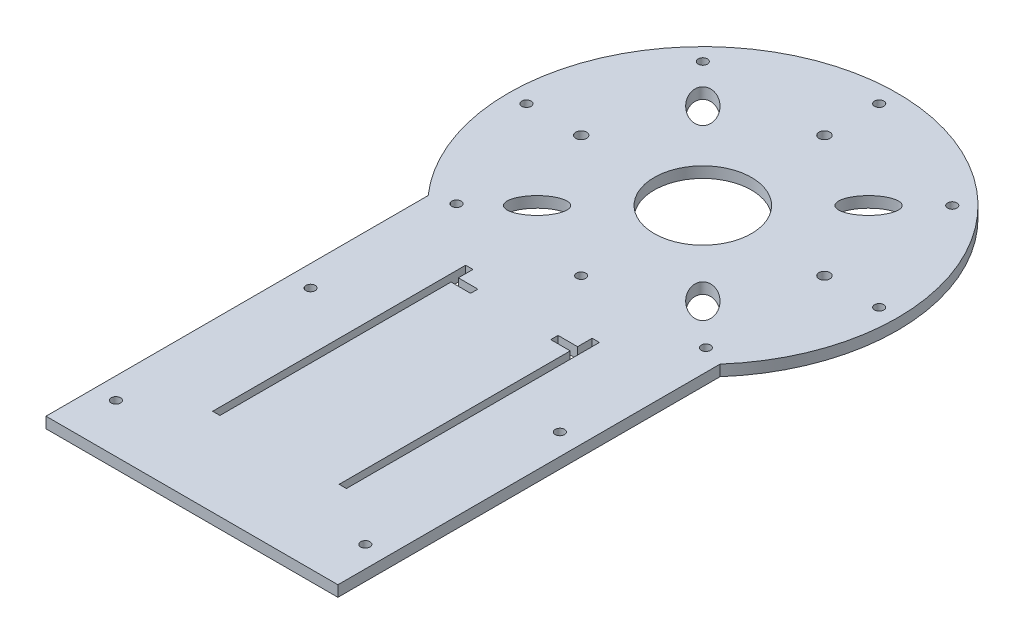
SolidWorks part; units mm, degrees
material "Acrylic (Medium-high impact)"
ref_plane "Front Plane" through (0, 0, 0) normal (0, 0, 1) x (1, 0, 0)
ref_plane "Top Plane" through (0, 0, 0) normal (0, 1, 0) x (1, 0, 0)
ref_plane "Right Plane" through (0, 0, 0) normal (1, 0, 0) x (0, 0, -1)
sketch "Sketch1" plane through (0, 0, 0) normal (0, 1, 0) x (1, 0, 0)
  line L0 (-51.25, 140) -> (-51.25, 0) construction
  line L1 (0, 0) -> (-102.5, 0) construction
  line L2 (0, 0) -> (0, 140) construction
  line L3 (0, 140) -> (-102.5, 140) construction
  line L4 (-102.5, 0) -> (-102.5, 140) construction
  line L5 (-34.78, 114) -> (-34.78, 111)
  line L6 (-78.75, 16) -> (-75.75, 16)
  line L7 (-78.75, 16) -> (-78.75, 120)
  line L8 (-78.75, 120) -> (-75.75, 120)
  line L9 (-75.75, 16) -> (-75.75, 120)
  line L10 (-75.75, 114) -> (-67.72, 114)
  line L11 (-75.75, 114) -> (-75.75, 111)
  line L12 (-75.75, 111) -> (-67.72, 111)
  line L13 (-67.72, 114) -> (-67.72, 111)
  line L14 (-26.75, 111) -> (-34.78, 111)
  line L15 (-26.75, 114) -> (-26.75, 111)
  line L16 (-26.75, 114) -> (-34.78, 114)
  line L17 (-26.75, 16) -> (-26.75, 120)
  line L18 (-23.75, 120) -> (-26.75, 120)
  line L19 (-23.75, 16) -> (-23.75, 120)
  line L20 (-23.75, 16) -> (-26.75, 16)
  line L21 (8.75, 140) -> (8.75, -20)
  line L22 (-51.25, 140) -> (-111.25, 140)
  line L23 (-51.25, 140) -> (-51.25, -20) construction
  line L24 (8.75, -20) -> (-111.25, -20)
  line L25 (-111.25, 140) -> (-111.25, -20)
  line L26 (-51.25, 190) -> (-51.25, 270) construction
  line L27 (-51.25, 190) -> (-107.8185, 246.5685) construction
  line L28 (-107.8185, 246.5685) -> (5.3185, 246.5685) construction
  line L29 (-107.8185, 133.4315) -> (5.3185, 246.5685) construction
  line L30 (-51.25, 190) -> (5.3185, 133.4315) construction
  line L31 (-51.25, 190) -> (-123.75, 190) construction
  line L32 (-51.25, 190) -> (-102.5152, 241.2652) construction
  circle A0 centre (-102.5, 140) radius 1.905
  circle A1 centre (0, 140) radius 1.905
  circle A2 centre (-102.5, 0) radius 1.905
  circle A3 centre (0, 0) radius 1.905
  circle A4 centre (-102.5, 80) radius 1.905
  circle A5 centre (0, 80) radius 1.905
  circle A6 centre (-51.25, 140) radius 1.905
  circle A7 centre (-51.25, 190) radius 80
  circle A8 centre (-51.25, 190) radius 20
  circle A9 centre (-51.25, 240) radius 2.25
  circle A10 centre (-1.25, 190) radius 2.25
  circle A12 centre (-101.25, 190) radius 2.25
  circle A13 centre (-51.25, 190) radius 72.5 construction
  circle A14 centre (-123.75, 190) radius 1.905
  circle A15 centre (-102.5152, 241.2652) radius 1.905
  circle A16 centre (-51.25, 262.5) radius 1.905
  circle A17 centre (0.0152, 241.2652) radius 1.905
  circle A18 centre (21.25, 190) radius 1.905
  circle A19 centre (-51.25, 140) radius 2.25 [skipped]
  ellipse E0 centre (-86.6053, 225.3553) end of major axis (-93.5201, 232.2701) minor radius 5
  ellipse E1 centre (-17.1818, 224.0682) end of major axis (-10.267, 230.983) minor radius 5
  ellipse E2 centre (-17.1818, 155.9318) end of major axis (-10.267, 149.017) minor radius 5
  ellipse E3 centre (-85.3182, 155.9318) end of major axis (-92.233, 149.017) minor radius 5
  point P32 (-51.25, 190)
  point P53 (-51.25, 190)
  point P96 (-51.25, 190)
  dimension "D3" = 3.81
  dimension "D4" = 3.81
  dimension "D5" = 3.81
  dimension "D6" = 3.81
  dimension "D7" = 3.81
  dimension "D8" = 3.81
  dimension "D11" = 3.81
  dimension "D19" = 160
  dimension "D22" = 40
  dimension "D24" = 4.5
  dimension "D28" = 145
  dimension "D29" = 3.81
  dimension "D1" = 102.5
  dimension "D2" = 140
  dimension "D9" = 60
  dimension "D10" = 60
  dimension "D12" = 32
  dimension "D13" = 3
  dimension "D14" = 55
  dimension "D15" = 104
  dimension "D16" = 3
  dimension "D17" = 6
  dimension "D18" = 50
  dimension "D20" = 60
  dimension "D21" = 160
  dimension "D23" = 50
  dimension "D26" = 45
  dimension "D27" = 45
  dimension "D31" = 45
  dimension "D32" = 50
  dimension "D25" = 4
  dimension "D30" = 5
extrude "Boss-Extrude1" add sketch "Sketch1" along normal blind 4.5
